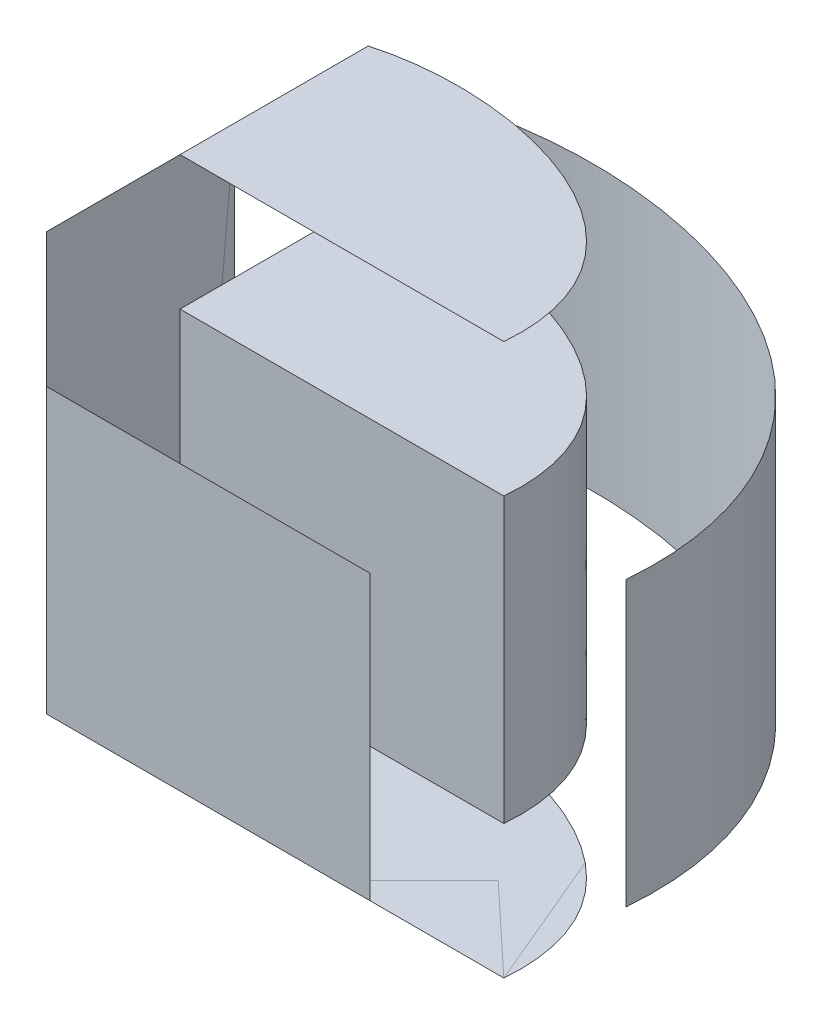
SolidWorks part; units mm, degrees
ref_plane "前视基准面" through (0, 0, 0) normal (0, 0, 1) x (1, 0, 0)
ref_plane "上视基准面" through (0, 0, 0) normal (0, 1, 0) x (1, 0, 0)
ref_plane "右视基准面" through (0, 0, 0) normal (1, 0, 0) x (0, 0, -1)
other "Configuration Table"
sketch "草图1" plane through (0, 0, 0) normal (0, 1, 0) x (1, 0, 0)
  line L0 (59.7318, -38.427) -> (-61.3003, -38.427)
  line L1 (-61.3003, -38.427) -> (-61.3003, 31.8918)
  spline S0 degree 3 poles (-61.3003, 31.8918) (-14.9359, 45.2018) (65.1709, 25.3085) (59.7318, -38.427) knots 0 0 0 0 1 1 1 1
extrude "凸台-拉伸1" add sketch "草图1" along normal mid plane 106
surface "曲面-等距1" parameters "D1"=50
surface "曲面-等距2" parameters "D1"=50
surface "曲面-等距5" parameters "D1"=50
surface "曲面-等距6" parameters "D1"=50
